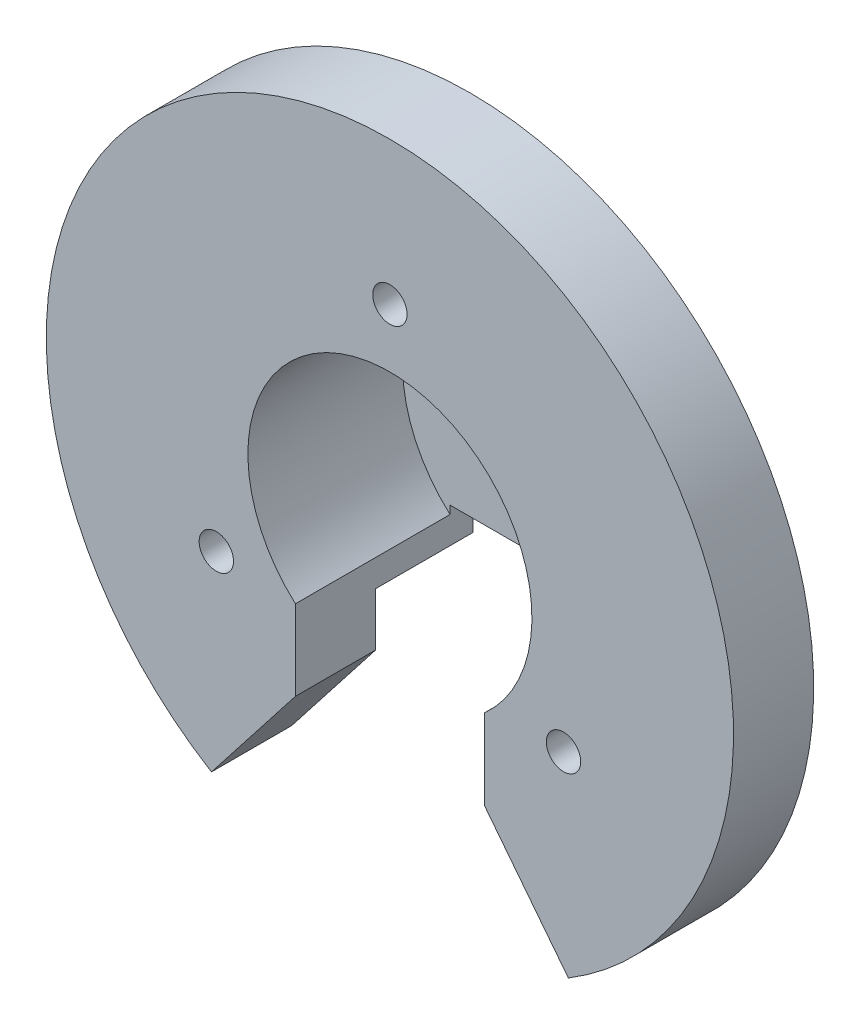
SolidWorks part; units mm, degrees
ref_plane "前视基准面" through (0, 0, 0) normal (0, 0, 1) x (1, 0, 0)
ref_plane "上视基准面" through (0, 0, 0) normal (0, 1, 0) x (1, 0, 0)
ref_plane "右视基准面" through (0, 0, 0) normal (1, 0, 0) x (0, 0, -1)
other "Configuration Table"
sketch "草图1" plane through (0, 0, 0) normal (0, 0, 1) x (1, 0, 0)
  circle A0 centre (0, 0) radius 12.4
  circle A1 centre (0, 0) radius 14.25
  dimension "D1" = 24.8
  dimension "D2" = 28.5
extrude "凸台-拉伸1" add sketch "草图1" along normal blind 13.5
sketch "草图2" plane through (0, 0, 0) normal (0, 0, -1) x (-1, 0, 0)
  line L0 (0, 0) -> (-10, 0)
  circle A0 centre (0, 0) radius 14.25
  circle A1 centre (0, 0) radius 4.5
  circle A2 centre (-10, 0) radius 1.5
  dimension "D1" = 9
  dimension "D3" = 3
  dimension "D2" = 10
extrude "凸台-拉伸2" add sketch "草图2" along normal blind 2
sketch "草图5" plane through (0, 0, 13.5) normal (0, 0, 1) x (1, 0, 0)
  circle A0 centre (0, 0) radius 30
  circle A1 centre (0, 0) radius 12.4
  dimension "D1" = 60
extrude "凸台-拉伸3" add sketch "草图5" against normal blind 2
sketch "草图4" plane through (0, 0, 13.5) normal (0, 0, 1) x (1, 0, 0)
  line L0 (-8.25, -16.2559) -> (-15.5796, -25.6374)
  line L1 (-8.25, -16.2559) -> (8.25, -16.2559) construction
  line L2 (-8.25, -16.2559) -> (-8.25, -8.5441)
  line L3 (-8.25, -8.5441) -> (8.25, -8.5441)
  line L4 (8.25, -16.2559) -> (8.25, -8.5441)
  line L5 (-8.25, -16.2559) -> (8.25, -8.5441) construction
  line L6 (-8.25, -8.5441) -> (8.25, -16.2559) construction
  line L7 (-15.5796, -25.6374) -> (-4.2428, -33.7786)
  line L8 (-4.2428, -33.7786) -> (18.3833, -29.2259)
  line L9 (18.3833, -29.2259) -> (8.25, -16.2559)
  circle A0 centre (0, 0) radius 12.4 construction
  circle A1 centre (0, 0) radius 12.4 construction
  circle A2 centre (0, 0) radius 30 construction
  point P0 (0, -12.4)
  dimension "D1" = 16.5
  dimension "D2" = 142
  dimension "D3" = 142
extrude "切除-拉伸2" cut sketch "草图4" against normal blind 19 and the other way blind 2
sketch "草图6" plane through (0, 0, 13.5) normal (0, 0, 1) x (1, 0, 0)
  circle A0 centre (0, 0) radius 17.5 construction
  circle A1 centre (0, 17.5) radius 1.5
  circle A2 centre (15.1554, -8.75) radius 1.5
  circle A3 centre (-15.1554, -8.75) radius 1.5
  point P11 (0, 0)
  dimension "D1" = 35
  dimension "D2" = 3
  dimension "D3" = 3
extrude "切除-拉伸3" cut sketch "草图6" against normal blind 2
sketch "草图8" plane through (0, 0, 11.5) normal (0, 0, -1) x (-1, 0, 0)
  line L4 (8.25, -11.619) -> (8.25, -16.2559)
  line L5 (8.25, -16.2559) -> (15.5796, -25.6374)
  line L6 (-15.5796, -25.6374) -> (-8.25, -16.2559)
  line L7 (-8.25, -16.2559) -> (-8.25, -11.619)
  line L8 (8.25, -11.619) -> (8.25, -16.2559)
  line L9 (8.25, -16.2559) -> (15.5796, -25.6374)
  line L10 (-15.5796, -25.6374) -> (-8.25, -16.2559)
  line L11 (-8.25, -16.2559) -> (-8.25, -11.619)
  circle A0 centre (0, 17.5) radius 1.5 construction
  circle A1 centre (-15.1554, -8.75) radius 1.5 construction
  arc A2 (15.5796, -25.6374) -> (-15.5796, -25.6374) centre (0, 0) ccw
  arc A3 (8.25, -11.619) -> (-8.25, -11.619) centre (0, 0) ccw
  arc A4 (15.5796, -25.6374) -> (-15.5796, -25.6374) centre (0, 0) ccw
  arc A5 (8.25, -11.619) -> (-8.25, -11.619) centre (0, 0) ccw
  circle A6 centre (15.1554, -8.75) radius 1.5 construction
  circle A7 centre (0, 17.5) radius 1.5
  circle A8 centre (-15.1554, -8.75) radius 1.5
  circle A9 centre (15.1554, -8.75) radius 1.5
  dimension "D1" = 0
extrude "凸台-拉伸4" add sketch "草图8" along normal blind 5
